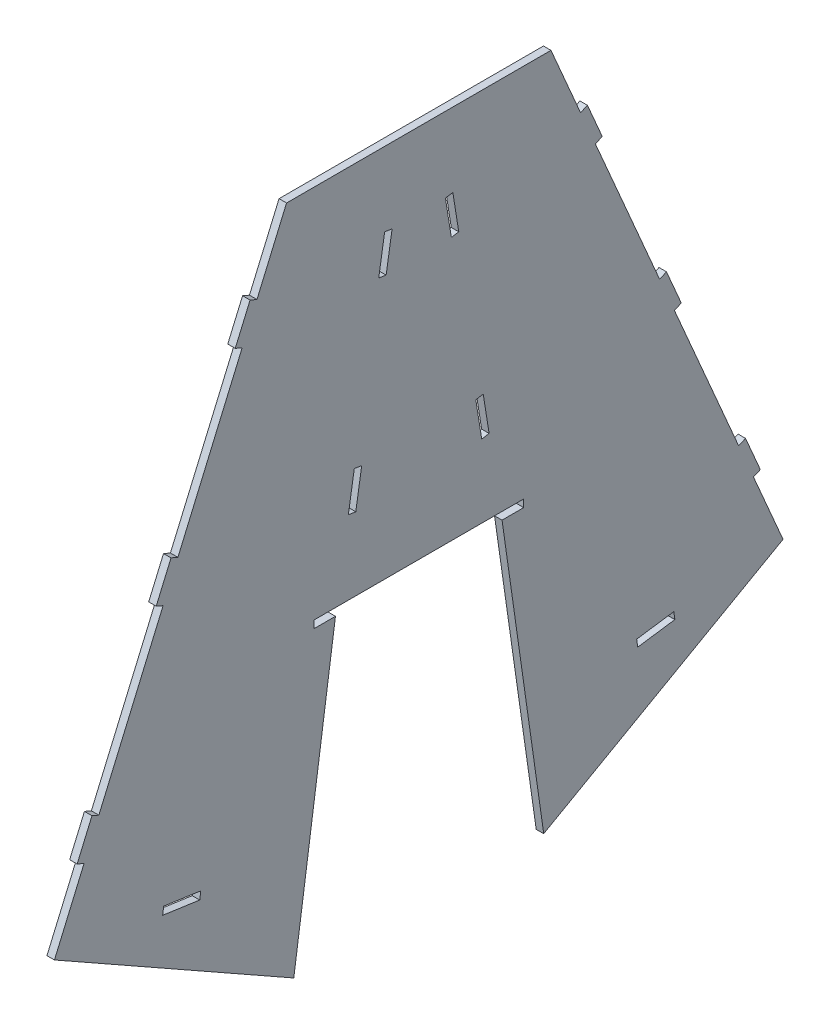
SolidWorks part; units mm, degrees
ref_plane "Front Plane" through (0, 0, 0) normal (0, 0, 1) x (1, 0, 0)
ref_plane "Top Plane" through (0, 0, 0) normal (0, 1, 0) x (1, 0, 0)
ref_plane "Right Plane" through (0, 0, 0) normal (1, 0, 0) x (0, 0, -1)
sketch "Sketch2" plane through (0, 0, 0) normal (1, 0, 0) x (0, 0, -1)
  line L2 (0, 0) -> (-95.762, 54.1261)
  line L3 (80, 120) -> (20, 120)
  line L13 (-2.8996, 270) -> (-14.7395, 242.4761)
  line L16 (16.6729, 117) -> (0, 0)
  line L18 (-52.2945, 155.1734) -> (-77.9947, 95.4292)
  line L19 (-55.0503, 156.3589) -> (-49.1229, 170.1381)
  line L20 (-49.1229, 170.1381) -> (-46.3671, 168.9526)
  line L21 (-55.0503, 156.3589) -> (-52.2945, 155.1734)
  line L22 (-20.6669, 228.6969) -> (-23.4228, 229.8824)
  line L23 (-23.4228, 229.8824) -> (-17.4954, 243.6616)
  line L24 (-17.4954, 243.6616) -> (-14.7395, 242.4761)
  line L25 (-2.8996, 270) -> (102.8996, 270)
  line L26 (-86.6779, 82.8354) -> (-83.9221, 81.65)
  line L27 (-80.7505, 96.6146) -> (-86.6779, 82.8354)
  line L28 (-77.9947, 95.4292) -> (-80.7505, 96.6146)
  line L38 (-20.6669, 228.6969) -> (-46.3671, 168.9526)
  line L39 (-83.9221, 81.65) -> (-95.762, 54.1261)
  line L48 (24.21, 164.4348) -> (21.8401, 149.6232)
  line L49 (36.3607, 240.3768) -> (33.9909, 225.5652)
  line L51 (36.3607, 240.3768) -> (39.323, 239.9028)
  line L52 (39.323, 239.9028) -> (36.9532, 225.0912)
  line L53 (36.9532, 225.0912) -> (33.9909, 225.5652)
  line L55 (27.1723, 163.9609) -> (24.21, 164.4348)
  line L56 (21.8401, 149.6232) -> (24.8025, 149.1492)
  line L57 (24.8025, 149.1492) -> (27.1723, 163.9609)
  line L64 (20, 120) -> (8, 120)
  line L67 (8, 117) -> (8, 120)
  line L68 (16.6729, 117) -> (8, 117)
  line L71 (83.3271, 117) -> (92, 117)
  line L72 (92, 117) -> (92, 120)
  line L73 (80, 120) -> (92, 120)
  line L74 (75.1975, 149.1492) -> (72.8277, 163.9609)
  line L75 (78.1599, 149.6232) -> (75.1975, 149.1492)
  line L76 (72.8277, 163.9609) -> (75.79, 164.4348)
  line L77 (63.0468, 225.0912) -> (66.0091, 225.5652)
  line L78 (60.677, 239.9028) -> (63.0468, 225.0912)
  line L79 (63.6393, 240.3768) -> (60.677, 239.9028)
  line L80 (63.6393, 240.3768) -> (66.0091, 225.5652)
  line L81 (75.79, 164.4348) -> (78.1599, 149.6232)
  line L82 (183.9221, 81.65) -> (195.762, 54.1261)
  line L83 (120.6669, 228.6969) -> (146.3671, 168.9526)
  line L84 (177.9947, 95.4292) -> (180.7505, 96.6146)
  line L85 (180.7505, 96.6146) -> (186.6779, 82.8354)
  line L86 (186.6779, 82.8354) -> (183.9221, 81.65)
  line L87 (117.4954, 243.6616) -> (114.7395, 242.4761)
  line L88 (123.4228, 229.8824) -> (117.4954, 243.6616)
  line L89 (120.6669, 228.6969) -> (123.4228, 229.8824)
  line L90 (155.0503, 156.3589) -> (152.2945, 155.1734)
  line L91 (149.1229, 170.1381) -> (146.3671, 168.9526)
  line L92 (155.0503, 156.3589) -> (149.1229, 170.1381)
  line L93 (152.2945, 155.1734) -> (177.9947, 95.4292)
  line L94 (83.3271, 117) -> (100, 0)
  line L95 (102.8996, 270) -> (114.7395, 242.4761)
  line L96 (100, 0) -> (195.762, 54.1261)
  line L97 (-52.4792, 47.9581) -> (-37.6292, 45.8419)
  line L98 (-52.0559, 50.9281) -> (-37.206, 48.8119)
  line L99 (-52.0559, 50.9281) -> (-52.4792, 47.9581)
  line L100 (-37.206, 48.8119) -> (-37.6292, 45.8419)
  line L101 (137.206, 48.8119) -> (137.6292, 45.8419)
  line L102 (152.0559, 50.9281) -> (152.4792, 47.9581)
  line L103 (152.0559, 50.9281) -> (137.206, 48.8119)
  line L104 (152.4792, 47.9581) -> (137.6292, 45.8419)
  point P15 (-16.1174, 243.0688)
  point P37 (50, 120)
  dimension "D2" = 100
  dimension "D3" = 30
  dimension "D4" = 15
  dimension "D5" = 120
  dimension "D6" = 68.635
  dimension "D7" = 110
  dimension "D8" = 12
  dimension "D9" = 3
  dimension "D10" = 3
  dimension "D11" = 235
  dimension "D12" = 3
  dimension "D13" = 15
  dimension "D14" = 30
extrude "Boss-Extrude1" add sketch "Sketch2" along normal blind 3
